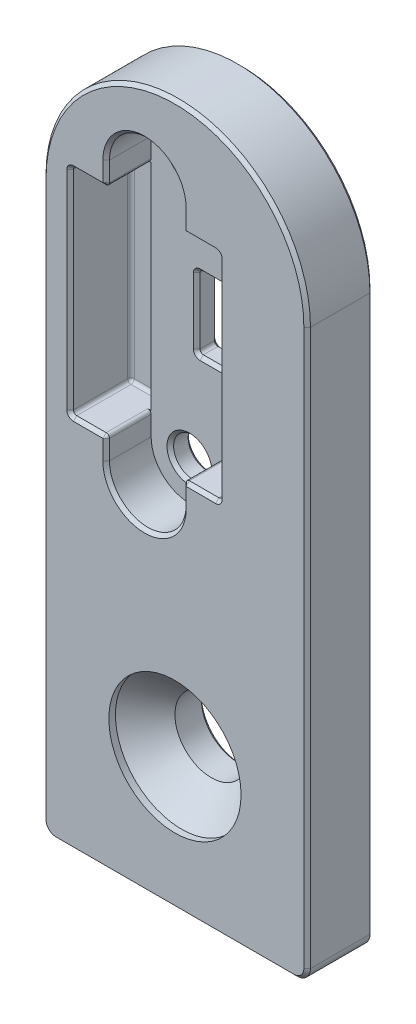
SolidWorks part; units mm, degrees
ref_plane "Front Plane" through (0, 0, 0) normal (0, 0, 1) x (1, 0, 0)
ref_plane "Top Plane" through (0, 0, 0) normal (0, 1, 0) x (1, 0, 0)
ref_plane "Right Plane" through (0, 0, 0) normal (1, 0, 0) x (0, 0, -1)
sketch "Sketch1" plane through (0, 0, 0) normal (0, 0, 1) x (1, 0, 0)
  line L0 (-21.8994, 0) -> (21.4746, 0) construction
  line L1 (0, 20.9985) -> (0, -16.0644) construction
  line L2 (-10, 10) -> (10, 10) construction
  line L3 (-10, 43) -> (10, 43)
  line L4 (-10, 43) -> (-10, -10)
  line L5 (-10, -10) -> (10, -10)
  line L6 (10, 43) -> (10, -10)
  line L7 (-10, 43) -> (10, -10) construction
  line L8 (-10, -10) -> (10, 43) construction
  line L9 (-10, 10) -> (10, -10) construction
  line L10 (-10, 10) -> (-10, -10) construction
  line L11 (-10, 10) -> (10, 43) construction
  circle A1 centre (0, 0) radius 2.75
  circle A2 centre (0, 33) radius 10
  point P4 (0, 16.5)
  point P12 (0, 0)
  point P13 (0, 26.5)
  dimension "D4" = 5.5
  dimension "D1" = 20
  dimension "D2" = 33
extrude "Boss-Extrude1" add sketch "Sketch1" along normal blind 5
hole_wizard "CSK for M5 Flat Head Machine Screw1" positions "Sketch3" profile "Sketch4" countersink size "M5" standard "ANSI Metric" end condition through all
sketch "Sketch3" plane through (0, 0, 5) normal (0, 0, 1) x (1, 0, 0)
  point P0 (0, 0)
sketch "Sketch4" plane through (0, 0, 5) normal (1, 0, 0) x (0, -1, 0)
  line L0 (0, 0) -> (0, 5)
  line L1 (0, 5) -> (2.75, 5)
  line L2 (2.75, 5) -> (2.75, 2.75)
  line L3 (2.75, 2.75) -> (5, 0.5)
  line L4 (5, 0.5) -> (5, 0)
  line L6 (5, 0) -> (0, 0)
  line L7 (-2.75, 2.75) -> (-5, 0.5) construction
  line L11 (0, -6.35) -> (0, 107.95) construction
  dimension "Thru Hole Dia." = 5.5
  dimension "Thru Hole Depth" = 5
  dimension "C'Sink Dia." = 10
  dimension "C'Sink Angle" = 90
  dimension "Head Clearance" = 0.5
sketch "Sketch5" plane through (0, 0, 5) normal (0, 0, 1) x (1, 0, 0)
  line L0 (0, 39.621) -> (0, -14.9634) construction
  line L1 (-10, 10) -> (10, 10) construction
  line L2 (-10, 33) -> (-10, -10) construction
  line L3 (10, 33) -> (10, -10) construction
  line L4 (-10, -10) -> (10, -10) construction
  line L5 (-11.4083, 43) -> (12.5744, 43) construction
  line L6 (-10, 10) -> (-10, 43) construction
  line L7 (-17.2391, 26.5) -> (-4.1577, 26.5) construction
  line L8 (-2.3, 52.2713) -> (-2.3, 37.4231) construction
  circle A0 centre (-2.3, 36.35) radius 1.45
  circle A1 centre (-2.3, 16.65) radius 1.45
  arc A3 (10, 33) -> (-10, 33) centre (0, 33) ccw construction
  point P16 (0, 43)
  point P18 (-10, 26.5)
  dimension "D2" = 2.9
  dimension "D1" = 19.7
  dimension "D3" = 20
  dimension "D4" = 2.3
extrude "Cut-Extrude1" cut sketch "Sketch5" against normal up to next
sketch "Sketch6" plane through (0, 0, 5) normal (0, 0, 1) x (1, 0, 0)
  line L0 (-2.3, 36.35) -> (-2.3, 16.65) construction
  line L1 (-5.1394, 26.5) -> (1.0915, 26.5) construction
  line L2 (-5.2, 36.35) -> (-5.2, 34.625)
  line L3 (-7.925, 18.375) -> (3.325, 18.375)
  line L4 (-7.925, 18.375) -> (-7.925, 34.625)
  line L5 (-7.925, 34.625) -> (3.325, 34.625)
  line L6 (3.325, 18.375) -> (3.325, 34.625)
  line L7 (-7.925, 18.375) -> (3.325, 34.625) construction
  line L8 (-7.925, 34.625) -> (3.325, 18.375) construction
  line L9 (0.6, 36.35) -> (0.6, 34.625)
  line L10 (0.6, 16.65) -> (0.6, 18.375)
  line L11 (-5.2, 16.65) -> (-5.2, 18.375)
  circle A0 centre (-2.3, 36.35) radius 2.9
  circle A1 centre (-2.3, 16.65) radius 2.9
  point P6 (-2.3, 26.5)
  point P8 (-2.3, 26.5)
  dimension "D1" = 5.8
  dimension "D2" = 11.25
  dimension "D3" = 16.25
extrude "Cut-Extrude2" cut sketch "Sketch6" against normal blind 3.4
sketch "Sketch7" plane through (0, 0, 1.6) normal (0, 0, 1) x (1, 0, 0)
  line L1 (-7.925, 34.625) -> (-5.2, 34.625)
  line L2 (-7.925, 34.625) -> (-7.925, 18.375)
  line L3 (-7.925, 18.375) -> (-5.2, 18.375)
  line L4 (-5.2, 34.625) -> (-5.2, 18.375)
extrude "Cut-Extrude3" cut sketch "Sketch7" against normal blind 1.2
sketch "Sketch8" plane through (0, 0, 1.6) normal (0, 0, 1) x (1, 0, 0)
  line L0 (-7.925, 26.5) -> (3.325, 26.5) construction
  line L1 (-7.925, 34.625) -> (-7.925, 18.375) construction
  line L4 (-1.75, 29.25) -> (1.75, 29.25)
  line L5 (-1.75, 29.25) -> (-1.75, 23.75)
  line L6 (-1.75, 23.75) -> (1.75, 23.75)
  line L7 (1.75, 29.25) -> (1.75, 23.75)
  line L8 (-1.75, 29.25) -> (1.75, 23.75) construction
  line L9 (-1.75, 23.75) -> (1.75, 29.25) construction
  line L10 (3.325, 18.375) -> (3.325, 34.625) construction
  line L11 (-2.3, 36.35) -> (-2.3, 16.65) construction
  point P6 (0, 26.5)
  dimension "D1" = 3.5
  dimension "D2" = 5.5
  dimension "D3" = 2.3
extrude "Cut-Extrude4" cut sketch "Sketch8" against normal up to next
fillet "Fillet1" radius 1 2 edges at (10, -10, 2.5) (-10, -10, 2.5)
fillet "Fillet3" radius 0.25 14 edges at (1.75, 29.25, 0.8) (1.75, 23.75, 0.8) (-1.75, 23.75, 0.8) (-1.75, 29.25, 0.8) (0.6, 34.625, 3.3) (3.325, 34.625, 3.3) (3.325, 18.375, 3.3) (0.6, 18.375, 3.3) (-7.925, 18.375, 2.7) (-7.925, 34.625, 2.7) (-7.925, 26.5, 0.4) (-6.5625, 34.625, 0.4) (-5.2, 26.5, 0.4) (-6.5625, 18.375, 0.4)
chamfer "Chamfer2" distance 0.25 angle 45 53 edges at (0, 43, 5) (0, -10, 0) (-9.7071, -9.7071, 0) (9.7071, -9.7071, 0) (0, -10, 5) (-9.7071, -9.7071, 5) (9.7071, -9.7071, 5) (-6.5625, 34.625, 5) (-6.5625, 18.375, 5) (-7.925, 26.5, 5) (1.9625, 34.625, 5) (3.325, 26.5, 5) (1.9625, 18.375, 5) (0.6732, 34.6982, 5) (0.6732, 18.3018, 5) (-5.2732, 18.3018, 5) (-5.2732, 34.6982, 5) (1.75, 26.5, 1.6) (0, 23.75, 1.6) (-1.75, 26.5, 1.6) (0, 29.25, 1.6) (-1.75, 26.5, 0) (0, 29.25, 0) (-10, 12, 5) (1.75, 26.5, 0) (0, 23.75, 0) (-7.8518, 34.5518, 5) (-7.8518, 18.4482, 5) (3.2518, 18.4482, 5) (3.2518, 34.5518, 5) (-1.6768, 29.1768, 1.6) (-1.6768, 29.1768, 0) (1.6768, 29.1768, 1.6) (1.6768, 29.1768, 0) (1.6768, 23.8232, 1.6) (1.6768, 23.8232, 0) (-1.6768, 23.8232, 1.6) (-1.6768, 23.8232, 0) (-0.85, 36.35, 0) (-0.85, 16.65, 0) (-5.2, 17.3875, 5) (-0.85, 36.35, 1.6) (0.6, 35.6125, 5) (-0.85, 16.65, 1.6) (-2.3, 39.25, 5) (-5.2, 35.6125, 5) (-2.3, 13.75, 5) (0.6, 17.3875, 5) (10, 12, 5) (2.75, 0, 0) (-10, 12, 0) (0, 43, 0) (10, 12, 0)
sketch "Sketch9" [suppressed] plane through (0, 0, 0) normal (0, 0, -1) x (-1, 0, 0)
  line L0 (-9.75, 33) -> (-9.75, -9) construction
  line L1 (-9, -9.75) -> (9, -9.75) construction
  line L2 (9.75, -9) -> (9.75, 33) construction
  line L3 (-9.75, 33) -> (-9.75, -9)
  line L4 (-9, -9.75) -> (9, -9.75)
  line L5 (9.75, -9) -> (9.75, 33)
  arc A0 (-9.75, -9) -> (-9, -9.75) centre (-9, -9) ccw construction
  arc A1 (9, -9.75) -> (9.75, -9) centre (9, -9) ccw construction
  arc A2 (9.75, 33) -> (-9.75, 33) centre (0, 33) ccw construction
  arc A3 (-9.75, -9) -> (-9, -9.75) centre (-9, -9) ccw
  arc A4 (9, -9.75) -> (9.75, -9) centre (9, -9) ccw
  arc A5 (9.75, 33) -> (-9.75, 33) centre (0, 33) ccw
  circle A8 centre (0, 0) radius 5 construction
  circle A9 centre (0, 0) radius 5
extrude "Boss-Extrude2" [suppressed] add sketch "Sketch9" against normal up to surface (5 mm away)
